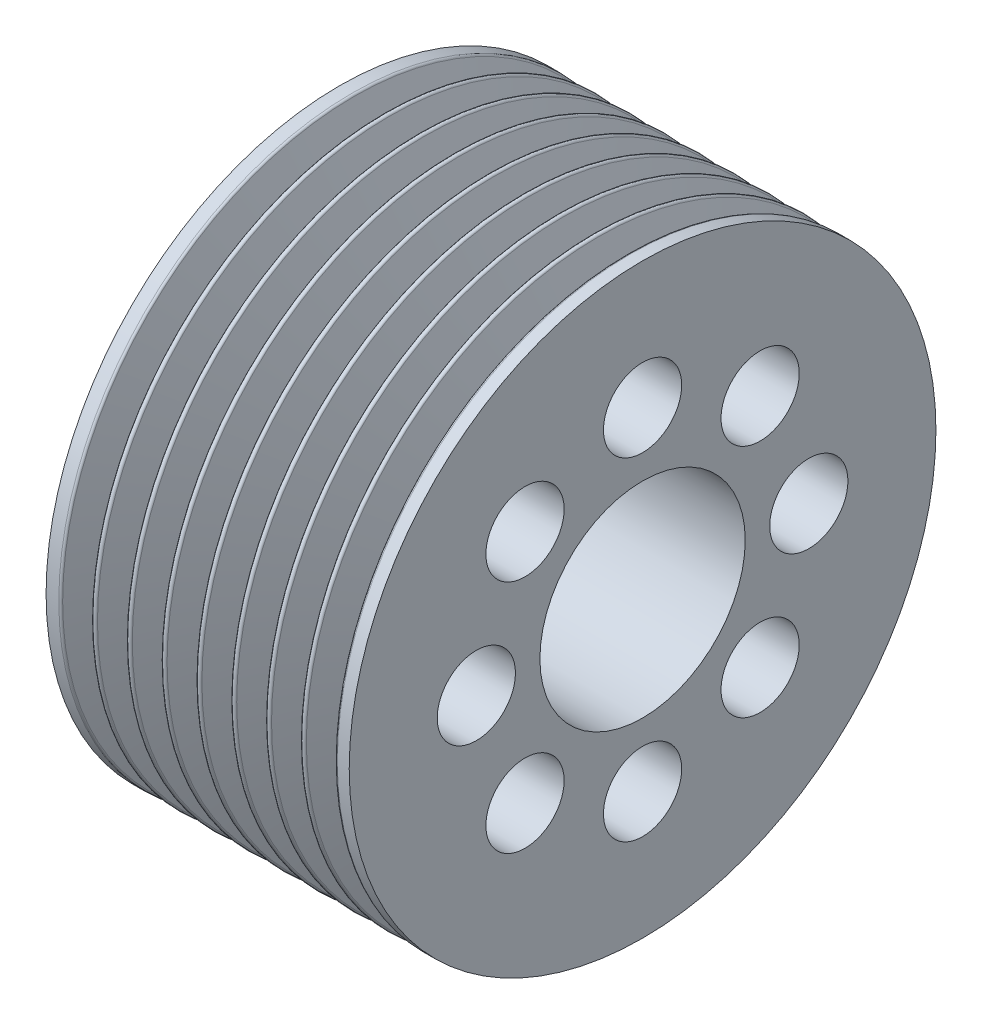
SolidWorks part; units mm, degrees
material "2018 Alloy"
ref_plane "Front Plane" through (0, 0, 0) normal (0, 0, 1) x (1, 0, 0)
ref_plane "Top Plane" through (0, 0, 0) normal (0, 1, 0) x (1, 0, 0)
ref_plane "Right Plane" through (0, 0, 0) normal (1, 0, 0) x (0, 0, -1)
sketch "Sketch1" plane through (0, 0, 0) normal (0, 0, 1) x (1, 0, 0)
  line L0 (49, 10.5) -> (49, 0) construction
  line L1 (49, 10.5) -> (49, 30)
  line L2 (49, 30) -> (18, 30)
  line L3 (18, 30) -> (18, 21.5)
  line L4 (49, 10.5) -> (31.5, 10.5)
  line L5 (0, 0) -> (49, 0) construction
  line L6 (18, 21.5) -> (31.5, 21.5)
  line L8 (0, 8.3175) -> (0, 0) construction
  line L9 (31.5, 10.5) -> (31.5, 21.5)
  dimension "D1" = 31
  dimension "D2" = 60
  dimension "D3" = 31.5
  dimension "D4" = 43
  dimension "D5" = 49
  dimension "D8" = 21
revolve "Revolve1" add sketch "Sketch1" angle 360 about L5
sketch "Sketch2" plane through (0, 0, 0) normal (0, 0, 1) x (1, 0, 0)
  line L0 (47.5458, 29.8376) -> (46.281, 26.4546)
  line L1 (45.719, 26.4546) -> (44.4542, 29.8376)
  line L2 (47.5458, 29.8376) -> (47.6066, 30) construction
  line L3 (49, 30) -> (18, 30) construction
  line L4 (44.4542, 29.8376) -> (44.3934, 30) construction
  line L5 (49, -30) -> (49, 30) construction
  line L6 (47.78, 30) -> (44.22, 30)
  line L7 (0, 0) -> (49, 0) construction
  arc A0 (47.5458, 29.8376) -> (47.78, 30) centre (47.78, 29.75) cw
  arc A1 (44.4542, 29.8376) -> (44.22, 30) centre (44.22, 29.75) ccw
  arc A2 (46.281, 26.4546) -> (45.719, 26.4546) centre (46, 26.5597) cw
  dimension "D2" = 0.25
  dimension "D3" = 0.3
  dimension "D1" = 41
  dimension "D4" = 3.56
  dimension "D5" = 3
revolve "Cut-Revolve1" cut sketch "Sketch2" angle 360 about L7
pattern_linear "LPattern1" count 8 spacing 3.56 along (-1, 0, 0) of "Cut-Revolve1"
sketch "Sketch3" plane through (49, 0, 0) normal (1, 0, 0) x (0, 0, -1)
  circle A0 centre (0, 0) radius 17 construction
  circle A1 centre (0, 17) radius 4
  circle A2 centre (12.0208, 12.0208) radius 4
  circle A3 centre (17, 0) radius 4
  circle A4 centre (12.0208, -12.0208) radius 4
  circle A5 centre (0, -17) radius 4
  circle A6 centre (-12.0208, -12.0208) radius 4
  circle A7 centre (-17, 0) radius 4
  circle A8 centre (-12.0208, 12.0208) radius 4
  dimension "D1" = 34
  dimension "D2" = 8
  dimension "D3" = 8
extrude "Cut-Extrude1" cut sketch "Sketch3" against normal up to surface (17.5 mm away) up to face at (31.5, 0, 10.5)
